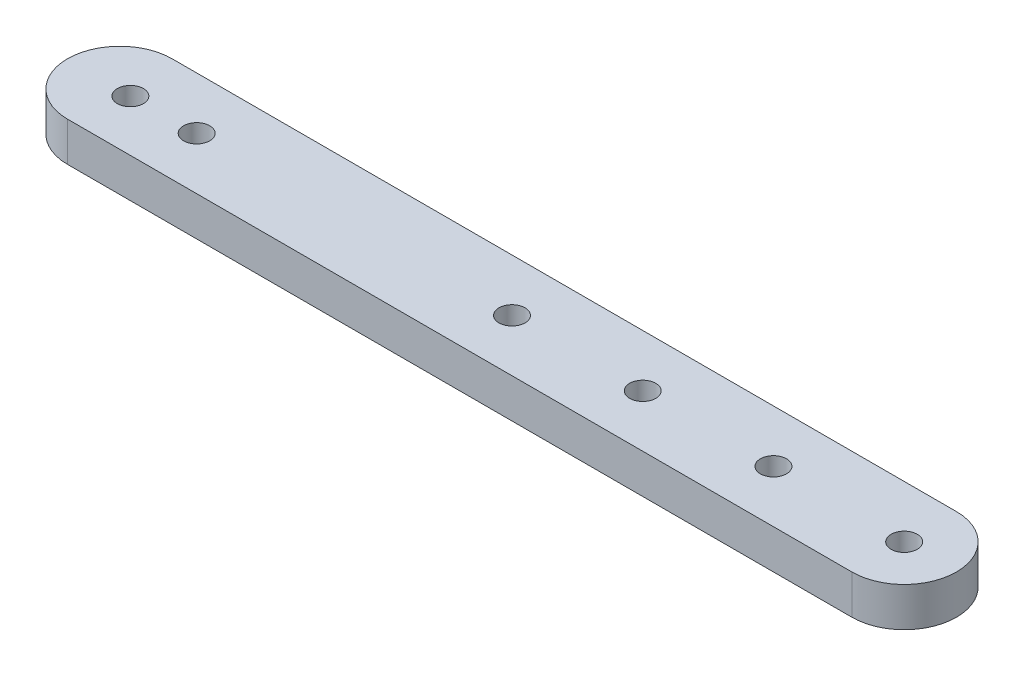
SolidWorks part; units mm, degrees
ref_plane "Front Plane" through (0, 0, 0) normal (0, 0, 1) x (1, 0, 0)
ref_plane "Top Plane" through (0, 0, 0) normal (0, 1, 0) x (1, 0, 0)
ref_plane "Right Plane" through (0, 0, 0) normal (1, 0, 0) x (0, 0, -1)
sketch "Sketch1" plane through (0, 0, 0) normal (0, 1, 0) x (1, 0, 0)
  line L0 (-56.2508, 0) -> (60, 0) construction
  line L1 (-60, -8) -> (60, -8)
  line L3 (-60, 8) -> (60, 8)
  line L11 (0, 8) -> (0, -8) construction
  circle A2 centre (-58.2458, -0.141) radius 2
  circle A3 centre (60, 0) radius 2
  circle A4 centre (20, 0) radius 2
  arc A5 (-60, 8) -> (-60, -8) centre (-60, 0) ccw
  arc A7 (60, -8) -> (60, 8) centre (60, 0) ccw
  circle A8 centre (-48.2458, 0) radius 2
  circle A9 centre (40, 0) radius 2
  circle A10 centre (0, 0) radius 2
  point P0 (0, 0)
  point P17 (0, 0)
  dimension "D3" = 4
  dimension "D4" = 4
  dimension "D5" = 4
  dimension "D8" = 16
  dimension "D9" = 4
  dimension "D11" = 4
  dimension "D12" = 4
  dimension "D1" = 120
  dimension "D2" = 8
  dimension "D6" = 60
  dimension "D7" = 40
  dimension "D10" = 10
  dimension "D13" = 20
  dimension "D14" = 20
extrude "Boss-Extrude1" add sketch "Sketch1" along normal blind 6
